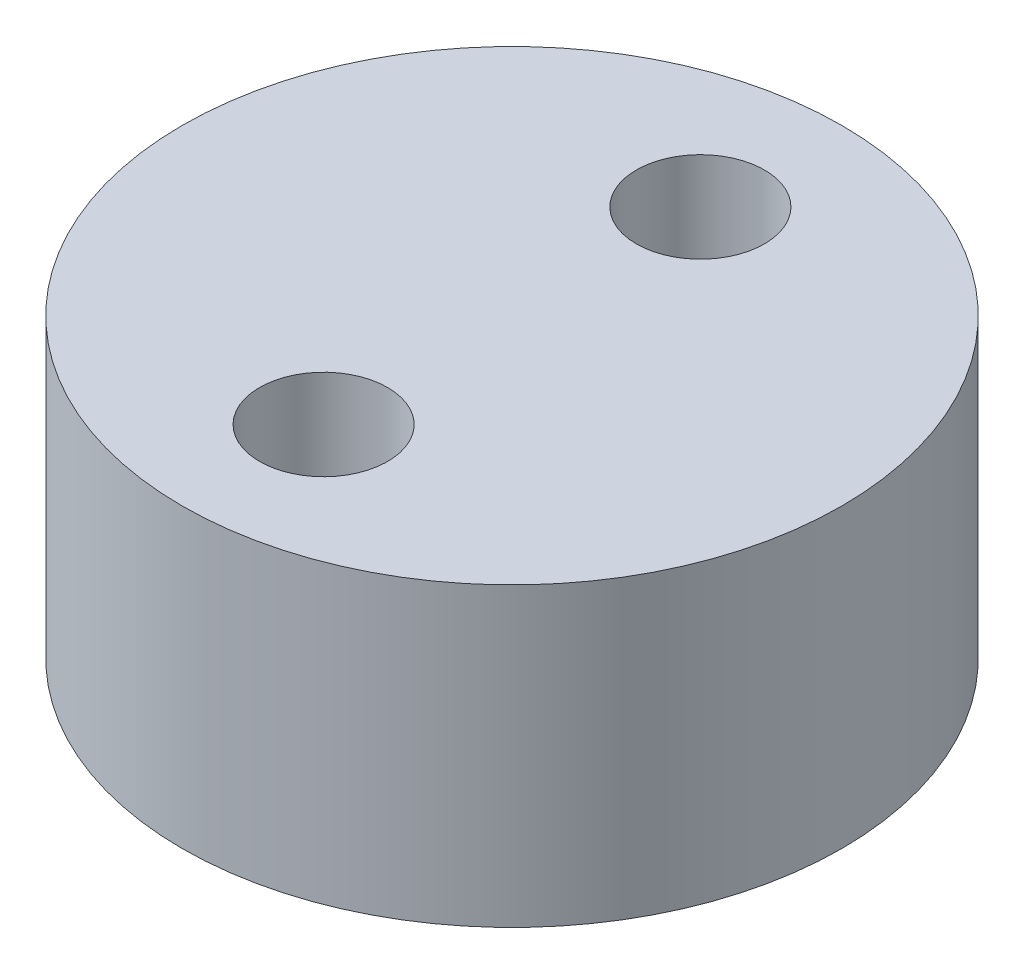
SolidWorks part; units mm, degrees
ref_plane "Front Plane" through (0, 0, 0) normal (0, 0, 1) x (1, 0, 0)
ref_plane "Top Plane" through (0, 0, 0) normal (0, 1, 0) x (1, 0, 0)
ref_plane "Right Plane" through (0, 0, 0) normal (1, 0, 0) x (0, 0, -1)
sketch "Sketch1" plane through (0, 0, 0) normal (0, 1, 0) x (1, 0, 0)
  line L0 (-11.1125, 0) -> (11.1125, 0) construction
  circle A0 centre (0, 0) radius 11.1125
  circle A1 centre (0, 6.35) radius 2.159
  circle A2 centre (0, -6.35) radius 2.159
  dimension "D1" = 4.318
  dimension "D3" = 22.225
  dimension "D2" = 6.35
extrude "Boss-Extrude1" add sketch "Sketch1" along normal blind 10
